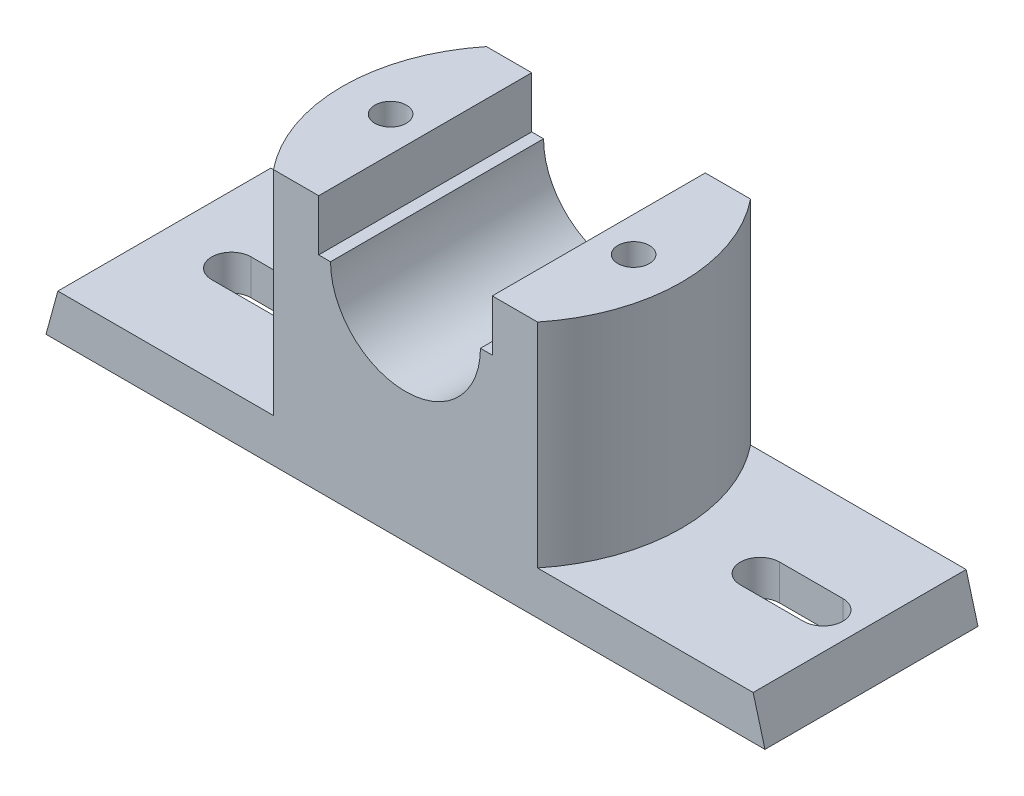
SolidWorks part; units mm, degrees
ref_plane "Front Plane" through (0, 0, 0) normal (0, 0, 1) x (1, 0, 0)
ref_plane "Top Plane" through (0, 0, 0) normal (0, 1, 0) x (1, 0, 0)
ref_plane "Right Plane" through (0, 0, 0) normal (1, 0, 0) x (0, 0, -1)
sketch "Sketch1" plane through (0, 0, 0) normal (0, 0, 1) x (1, 0, 0)
  line L1 (-95, 0) -> (87.2641, 0)
  line L2 (-95, 0) -> (-92, 11)
  line L3 (-92, 11) -> (84.2641, 11)
  line L4 (84.2641, 11) -> (87.2641, 0)
extrude "Boss-Extrude1" add sketch "Sketch1" along normal blind 54
sketch "Sketch2" plane through (0, 11, 0) normal (0, 1, 0) x (1, 0, 0)
  line L0 (84.2641, -54) -> (-92, -54) construction
  line L1 (84.2641, -54) -> (84.2641, 0)
  line L2 (84.2641, 0) -> (-92, 0) construction
  circle A0 centre (-3.8679, -27) radius 43
  point P4 (-3.8679, -27)
  line M1 (84.2641, 0) -> (-92, 0)
  line M3 (-92, -54) -> (84.2641, -54)
extrude "Boss-Extrude2" add sketch "Sketch2" along normal blind 54 contours A0 M3 M1
sketch "Sketch3" plane through (0, 0, 0) normal (0, 0, 1) x (1, 0, 0)
  line L0 (15.1321, 52) -> (18.1321, 52)
  line L1 (-37.3343, 65) -> (29.5985, 65) construction
  line L2 (-25.8679, 65) -> (-25.8679, 52)
  line L3 (-25.8679, 52) -> (-22.8679, 52)
  line L4 (18.1321, 65) -> (-25.8679, 65)
  line L7 (18.1321, 65) -> (18.1321, 52)
  arc A0 (-22.8679, 52) -> (15.1321, 52) centre (-3.8679, 52) ccw
extrude "Cut-Extrude4" cut sketch "Sketch3" against normal mid plane 159.9174
sketch "Sketch4" plane through (0, 0, 0) normal (0, 1, 0) x (1, 0, 0)
  circle A0 centre (-34.6465, -27) radius 4
  point P2 (0, 0)
extrude "Cut-Extrude8" cut sketch "Sketch4" along normal blind 120 and the other way blind 57
sketch "Sketch5" plane through (0, 0, 0) normal (0, 1, 0) x (1, 0, 0)
  circle A0 centre (26.963, -27) radius 4
extrude "Cut-Extrude10" cut sketch "Sketch5" along normal blind 155 and the other way blind 93
sketch "Sketch6" plane through (0, 11, 0) normal (0, 1, 0) x (1, 0, 0)
  line L0 (75, -27) -> (59, -27) construction
  line L1 (75, -32) -> (59, -32)
  line L2 (75, -22) -> (59, -22)
  line L3 (-59, -27) -> (-75, -27) construction
  line L4 (-59, -32) -> (-75, -32)
  line L5 (-59, -22) -> (-75, -22)
  arc A0 (75, -32) -> (75, -22) centre (75, -27) ccw
  arc A1 (59, -22) -> (59, -32) centre (59, -27) ccw
  arc A2 (-59, -32) -> (-59, -22) centre (-59, -27) ccw
  arc A3 (-75, -22) -> (-75, -32) centre (-75, -27) ccw
  point P2 (67, -27)
  point P9 (-67, -27)
extrude "Cut-Extrude11" cut sketch "Sketch6" against normal blind 155
sketch "Sketch7" plane through (0, 0, 0) normal (0, -1, 0) x (1, 0, 0)
  line L1 (-83.7257, 43.2305) -> (-21.1474, 43.2305)
  line L2 (-83.7257, 43.2305) -> (-83.7257, 8.7488)
  line L3 (-83.7257, 8.7488) -> (-21.1474, 8.7488)
  line L4 (-21.1474, 43.2305) -> (-21.1474, 8.7488)
  line L5 (9.9493, 10.335) -> (83.9734, 10.335)
  line L6 (9.9493, 10.335) -> (9.9493, 43.2305)
  line L7 (9.9493, 43.2305) -> (83.9734, 43.2305)
  line L8 (83.9734, 10.335) -> (83.9734, 43.2305)
extrude "Cut-Extrude12" cut sketch "Sketch7" against normal blind 2
